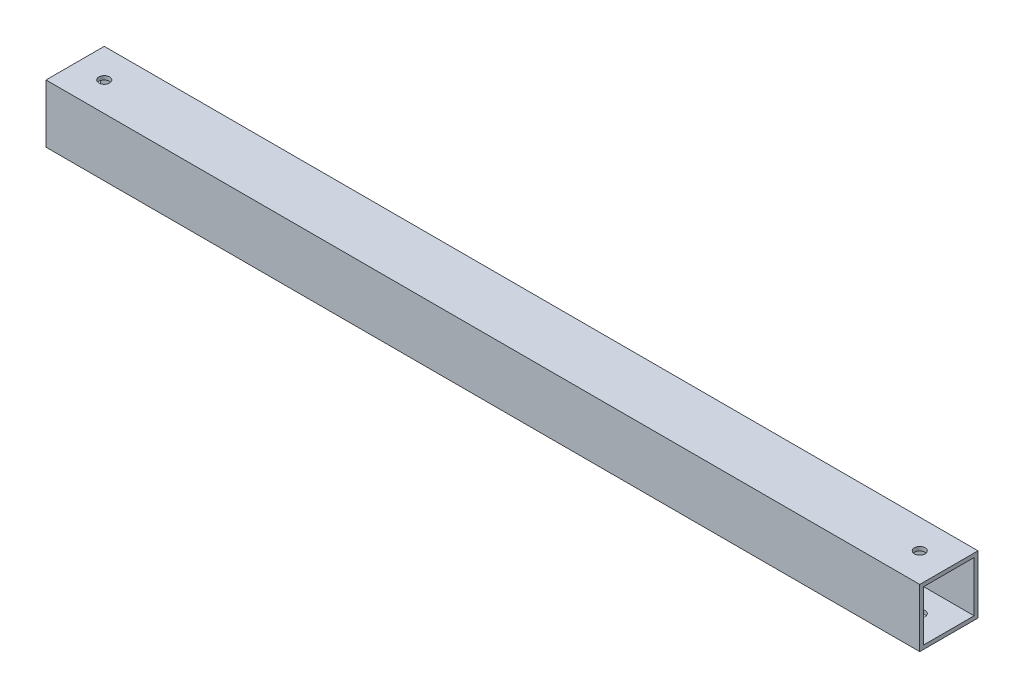
SolidWorks part; units mm, degrees
ref_plane "Front Plane" through (0, 0, 0) normal (0, 0, 1) x (1, 0, 0)
ref_plane "Top Plane" through (0, 0, 0) normal (0, 1, 0) x (1, 0, 0)
ref_plane "Right Plane" through (0, 0, 0) normal (1, 0, 0) x (0, 0, -1)
sketch "Sketch1" plane through (0, 0, 0) normal (1, 0, 0) x (0, 0, -1)
  line L1 (15, 15) -> (-15, 15)
  line L2 (15, 15) -> (15, -15)
  line L3 (15, -15) -> (-15, -15)
  line L4 (-15, 15) -> (-15, -15)
  line L5 (15, 15) -> (-15, -15) construction
  line L6 (15, -15) -> (-15, 15) construction
  line L7 (-13, 13) -> (13, 13)
  line L8 (-13, 13) -> (-13, -13)
  line L9 (-13, -13) -> (13, -13)
  line L10 (13, 13) -> (13, -13)
  line L11 (-13, 13) -> (13, -13) construction
  line L12 (-13, -13) -> (13, 13) construction
  point P0 (0, 0)
  point P5 (0, 0)
  dimension "D1" = 30
  dimension "D2" = 30
  dimension "D3" = 2
extrude "Boss-Extrude1" add sketch "Sketch1" along normal mid plane 450
sketch "Sketch2" plane through (0, 0, 0) normal (0, 1, 0) x (1, 0, 0)
  line L0 (225, 15) -> (225, -15) construction
  circle A0 centre (210, 0) radius 2.75
  dimension "D1" = 5.5
  dimension "D2" = 15
extrude "Cut-Extrude1" cut sketch "Sketch2" against normal through all both and the other way through all
mirror "Mirror1" about plane through (0, 0, 0) normal (1, 0, 0) of "Cut-Extrude1"
equation "\"D2@Sketch1\"=\"w\""
equation "\"D1@Sketch1\"=\"w\""
equation "\"t\"= 2"
equation "\"w\"= 30"
equation "\"D3@Sketch1\"=\"t\""
equation "\"D2@Sketch2\"=\"w\"/2"
